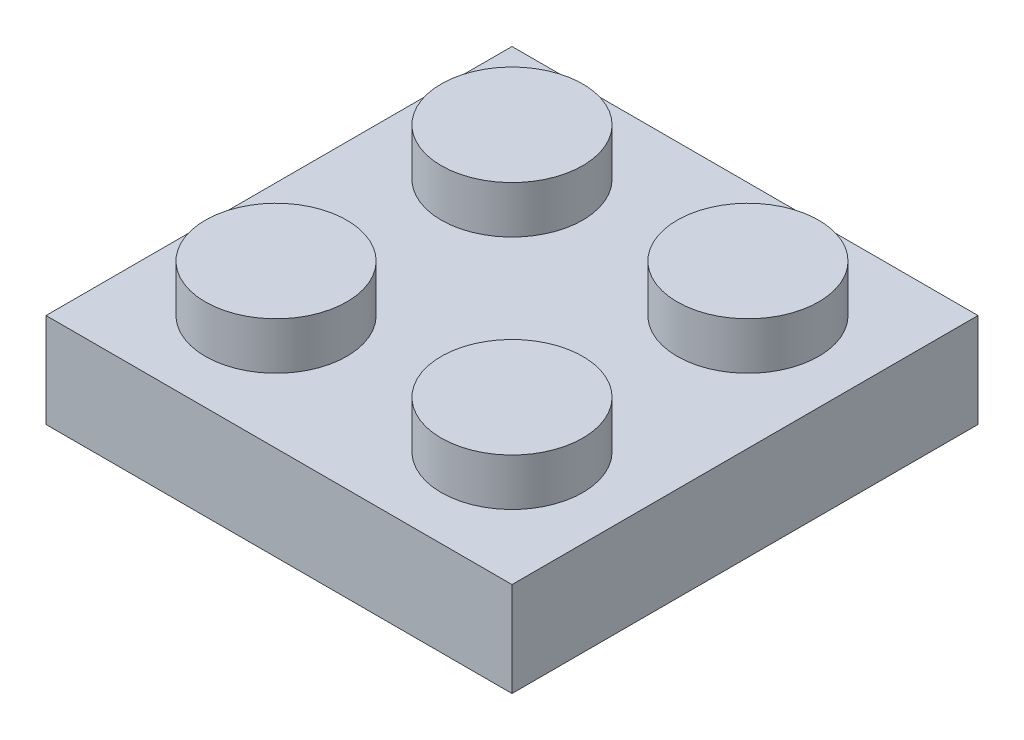
SolidWorks part; units mm, degrees
material "ABS"
ref_plane "Front Plane" through (0, 0, 0) normal (0, 0, 1) x (1, 0, 0)
ref_plane "Top Plane" through (0, 0, 0) normal (0, 1, 0) x (1, 0, 0)
ref_plane "Right Plane" through (0, 0, 0) normal (1, 0, 0) x (0, 0, -1)
sketch "Sketch1" plane through (0, 0, 0) normal (0, 0, 1) x (1, 0, 0)
  line L1 (0, 0) -> (15.8, 0)
  line L2 (0, 0) -> (0, 3.2)
  line L3 (0, 3.2) -> (15.8, 3.2)
  line L4 (15.8, 0) -> (15.8, 3.2)
  line L5 (0, 0) -> (15.8, 3.2) construction
  line L6 (0, 3.2) -> (15.8, 0) construction
  point P4 (7.9, 1.6)
  dimension "D1" = 15.8
  dimension "D2" = 3.2
extrude "Boss-Extrude1" add sketch "Sketch1" against normal blind 15.8
sketch "Sketch2" plane through (0, 3.2, 0) normal (0, 1, 0) x (1, 0, 0)
  line L0 (15.8, 0) -> (0, 0) construction
  circle A0 centre (3.9, 3.9) radius 2.4
  dimension "D1" = 4.8
  dimension "D2" = 3.9
  dimension "D3" = 3.9
extrude "Boss-Extrude2" add sketch "Sketch2" along normal blind 1.6
pattern_linear "LPattern1" count 2 spacing 8 along (0, 0, -1) count 4 spacing 8 along (1, 0, 0) of "Boss-Extrude2"
shell "Shell1" thickness 1.2
sketch "Sketch4" plane through (0, 2, 0) normal (0, -1, 0) x (1, 0, 0)
  line L0 (0, -15.8) -> (0, 0) construction
  line L1 (0, 0) -> (15.8, 0) construction
  circle A0 centre (7.9, -7.9) radius 3.25
  circle A1 centre (7.9, -7.9) radius 2.4
  dimension "D1" = 4.8
  dimension "D2" = 6.5
  dimension "D3" = 7.9
  dimension "D4" = 7.9
extrude "Boss-Extrude3" add sketch "Sketch4" along normal offset from surface (1.8 mm away) 0.2 up to face at (7.9, 0, -7.9)
